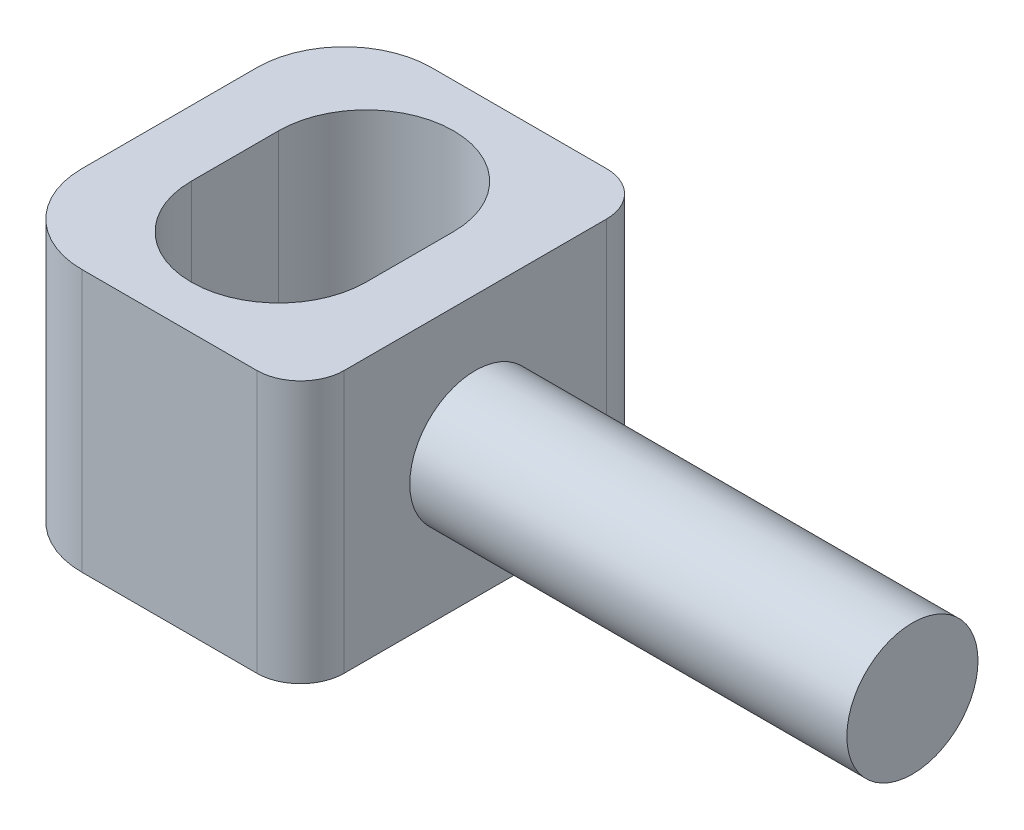
SolidWorks part; units mm, degrees
ref_plane "Front Plane" through (0, 0, 0) normal (0, 0, 1) x (1, 0, 0)
ref_plane "Top Plane" through (0, 0, 0) normal (0, 1, 0) x (1, 0, 0)
ref_plane "Right Plane" through (0, 0, 0) normal (1, 0, 0) x (0, 0, -1)
sketch "Sketch1" plane through (0, 0, 0) normal (0, 1, 0) x (1, 0, 0)
  line L0 (-12.5, 5) -> (-12.5, -5)
  line L1 (7.5, 5) -> (7.5, -5)
  line L2 (-10, 20) -> (10, 20)
  line L5 (-20, -10) -> (-20, 10)
  line L6 (-10, -20) -> (10, -20)
  line L7 (15, -15) -> (15, 15)
  arc A0 (-12.5, 5) -> (7.5, 5) centre (-2.5, 5) cw
  arc A1 (-12.5, -5) -> (7.5, -5) centre (-2.5, -5) ccw
  arc A2 (-20, 10) -> (-10, 20) centre (-10, 10) cw
  arc A3 (-10, -20) -> (-20, -10) centre (-10, -10) cw
  arc A4 (10, -20) -> (15, -15) centre (10, -15) ccw
  arc A5 (10, 20) -> (15, 15) centre (10, 15) cw
extrude "Boss-Extrude1" add sketch "Sketch1" along normal blind 30
sketch "Sketch2" plane through (15, 0, 0) normal (1, 0, 0) x (0, 0, -1)
  circle A0 centre (0, 15) radius 7.5
extrude "Boss-Extrude2" add sketch "Sketch2" along normal blind 50
